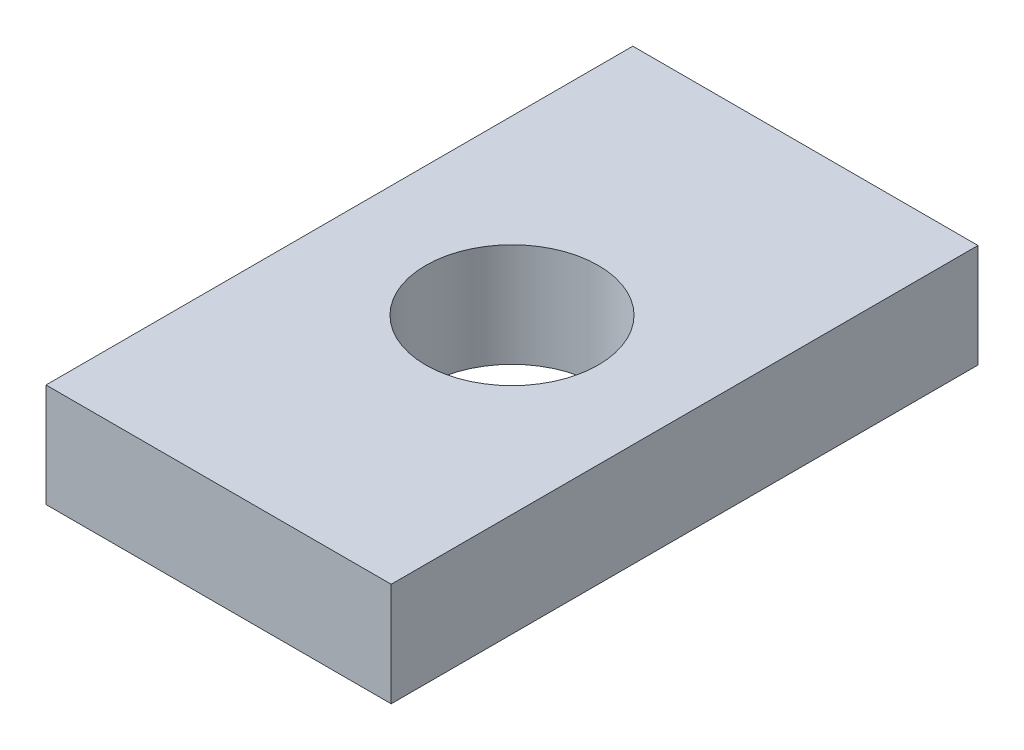
SolidWorks part; units mm, degrees
ref_plane "Front Plane" through (0, 0, 0) normal (0, 0, 1) x (1, 0, 0)
ref_plane "Top Plane" through (0, 0, 0) normal (0, 1, 0) x (1, 0, 0)
ref_plane "Right Plane" through (0, 0, 0) normal (1, 0, 0) x (0, 0, -1)
sketch "Sketch1" plane through (0, 0, 0) normal (0, 1, 0) x (1, 0, 0)
  line L1 (-10, 17) -> (10, 17)
  line L2 (-10, 17) -> (-10, -17)
  line L3 (-10, -17) -> (10, -17)
  line L4 (10, 17) -> (10, -17)
  line L5 (-10, 17) -> (10, -17) construction
  line L6 (-10, -17) -> (10, 17) construction
  circle A0 centre (0, 0) radius 5
  point P0 (0, 0)
  dimension "D3" = 10
  dimension "D1" = 20
  dimension "D2" = 34
extrude "Boss-Extrude1" add sketch "Sketch1" along normal blind 6
